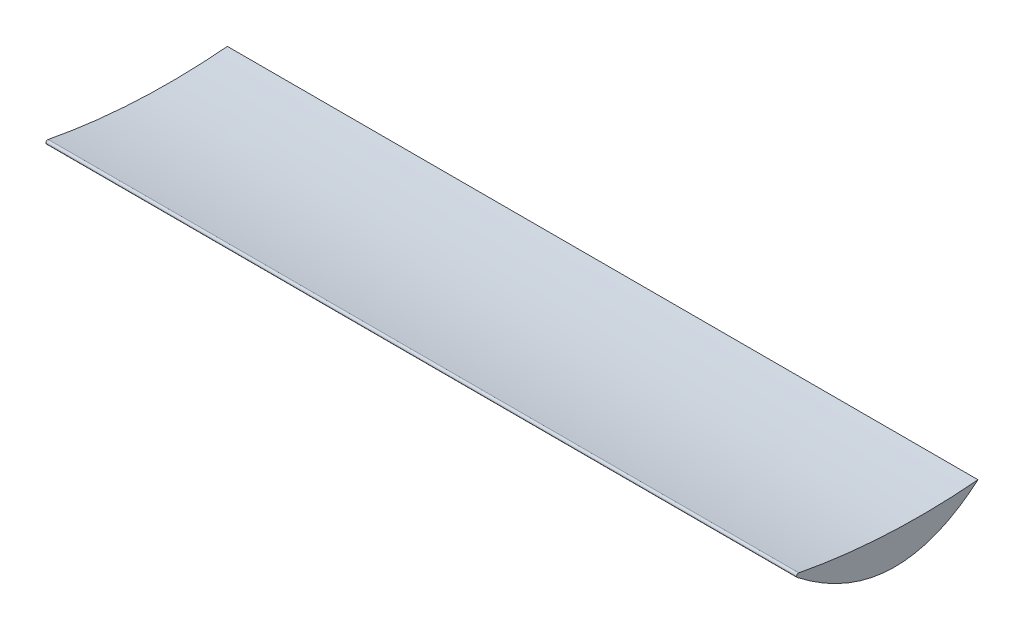
SolidWorks part; units mm, degrees
ref_plane "Front Plane" through (0, 0, 0) normal (0, 0, 1) x (1, 0, 0)
ref_plane "Top Plane" through (0, 0, 0) normal (0, 1, 0) x (1, 0, 0)
ref_plane "Right Plane" through (0, 0, 0) normal (1, 0, 0) x (0, 0, -1)
sketch "Sketch1" plane through (0, 0, 0) normal (1, 0, 0) x (0, 0, -1)
  spline S0 degree 2 poles (-120.5312, 22.7743) (4.4908, -2.6718) (132.1824, 8.6244) knots 0 0 0 1 1 1
  spline S1 degree 2 poles (132.1824, 8.6244) (17.0988, -89.8072) (-120.5312, 22.7743) knots 0 0 0 1 1 1
  point P0 (-120.5312, 22.7743)
  point P1 (132.1824, 8.6244)
  dimension "D1" = 254
extrude "Boss-Extrude1" add sketch "Sketch1" along normal blind 1016
fillet "Fillet1" radius 2.54 1 edges at (508, 22.7743, 120.5312)
